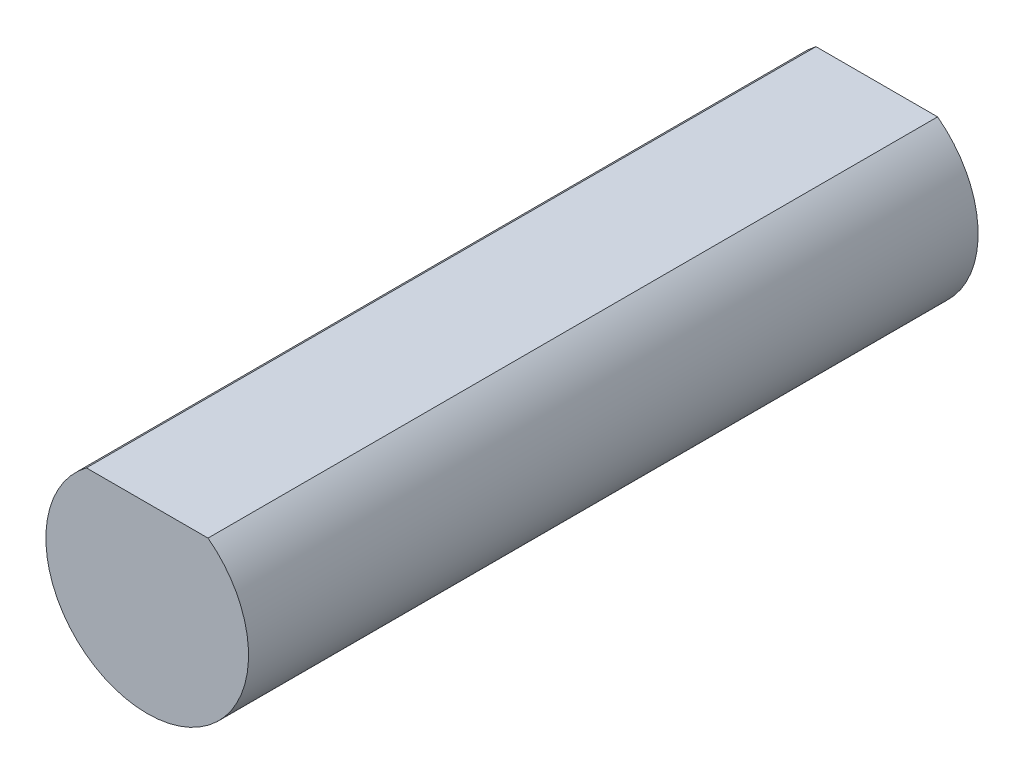
SolidWorks part; units mm, degrees
ref_plane "前视基准面" through (0, 0, 0) normal (0, 0, 1) x (1, 0, 0)
ref_plane "上视基准面" through (0, 0, 0) normal (0, 1, 0) x (1, 0, 0)
ref_plane "右视基准面" through (0, 0, 0) normal (1, 0, 0) x (0, 0, -1)
sketch "草图1" plane through (0, 0, 0) normal (0, 0, 1) x (1, 0, 0)
  line L0 (-1.5, 2) -> (1.5, 2)
  line L1 (-1000, -2.5) -> (49000, -2.5) construction
  circle A0 centre (0, 0) radius 2.5
  dimension "D1" = 5
  dimension "D2" = 4.5
extrude "凸台-拉伸1" add sketch "草图1" along normal blind 18 contours L0 A0
